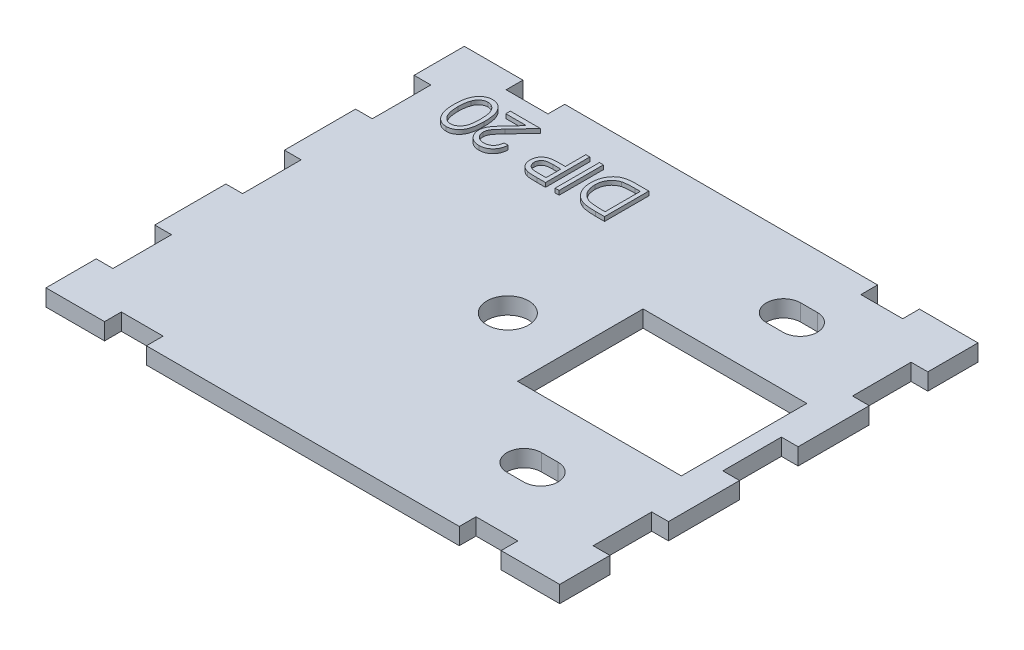
SolidWorks part; units mm, degrees
ref_plane "Front Plane" through (0, 0, 0) normal (0, 0, 1) x (1, 0, 0)
ref_plane "Top Plane" through (0, 0, 0) normal (0, 1, 0) x (1, 0, 0)
ref_plane "Right Plane" through (0, 0, 0) normal (1, 0, 0) x (0, 0, -1)
sketch "Sketch2" plane through (0, 0, 0) normal (0, 1, 0) x (1, 0, 0)
  line L1 (-50, 25) -> (50, 25)
  line L2 (-50, 25) -> (-50, -25)
  line L3 (-50, -25) -> (50, -25)
  line L4 (50, 25) -> (50, -25)
  line L5 (-50, 25) -> (50, -25) construction
  line L6 (-50, -25) -> (50, 25) construction
  point P0 (0, 0)
  dimension "D1" = 100
  dimension "D2" = 50
extrude "Boss-Extrude1" add sketch "Sketch2" along normal blind 2
sketch "Sketch12" plane through (0, 2, 0) normal (0, 1, 0) x (1, 0, 0)
  line L0 (-50, -25) -> (50, -25) construction
  line L1 (-40.2, -25) -> (-50, -25)
  line L2 (-40.2, -25) -> (-40.2, 25)
  line L3 (-40.2, 25) -> (-50, 25)
  line L4 (-50, -25) -> (-50, 25)
  line L5 (-50, -25) -> (50, -25) construction
  line L6 (41.2, -25) -> (50, -25)
  line L7 (41.2, -25) -> (41.2, 25)
  line L8 (41.2, 25) -> (50, 25)
  line L9 (50, -25) -> (50, 25)
extrude "Cut-Extrude8" cut sketch "Sketch12" against normal blind 6
sketch "Sketch13" plane through (0, 2, 0) normal (0, 1, 0) x (1, 0, 0)
  line L1 (-28.2, 19) -> (-30.2, 19)
  line L2 (-28.2, 19) -> (-28.2, 12)
  line L3 (-28.2, 12) -> (-30.2, 12)
  line L4 (-30.2, 19) -> (-30.2, 12)
  line L5 (-28.2, 3.5) -> (-30.2, 3.5)
  line L6 (-28.2, 3.5) -> (-28.2, -3.5)
  line L7 (-28.2, -3.5) -> (-30.2, -3.5)
  line L8 (-30.2, 3.5) -> (-30.2, -3.5)
  line L9 (-28.2, -12) -> (-30.2, -12)
  line L10 (-28.2, -12) -> (-28.2, -19)
  line L11 (-28.2, -19) -> (-30.2, -19)
  line L12 (-30.2, -12) -> (-30.2, -19)
  line L13 (29.2, 19) -> (31.2, 19)
  line L14 (29.2, 19) -> (29.2, 12)
  line L15 (29.2, 12) -> (31.2, 12)
  line L16 (31.2, 19) -> (31.2, 12)
  line L17 (29.2, 3.5) -> (31.2, 3.5)
  line L18 (29.2, 3.5) -> (29.2, -3.5)
  line L19 (29.2, -3.5) -> (31.2, -3.5)
  line L20 (31.2, 3.5) -> (31.2, -3.5)
  line L21 (29.2, -12) -> (31.2, -12)
  line L22 (29.2, -12) -> (29.2, -19)
  line L23 (29.2, -19) -> (31.2, -19)
  line L24 (31.2, -12) -> (31.2, -19)
  line L25 (-40.2, -25) -> (41.2, -25) construction
  line L26 (-23.2, 25) -> (-18.2, 25)
  line L27 (41.2, 25) -> (-40.2, 25) construction
  line L28 (-40.2, -25) -> (41.2, -25) construction
  line L29 (41.2, 25) -> (-40.2, 25) construction
  line L30 (-40.2, -25) -> (41.2, -25) construction
  line L31 (41.2, 25) -> (31.2, 25)
  line L32 (41.2, 25) -> (41.2, -25)
  line L33 (41.2, -25) -> (31.2, -25)
  line L34 (31.2, 25) -> (31.2, -25)
  line L35 (41.2, 25) -> (-40.2, 25) construction
  line L36 (-40.2, -25) -> (-30.2, -25)
  line L37 (-40.2, -25) -> (-40.2, 25)
  line L38 (-40.2, 25) -> (-30.2, 25)
  line L39 (-30.2, -25) -> (-30.2, 25)
  line L40 (-23.2, 25) -> (-23.2, 23)
  line L41 (-23.2, 23) -> (-18.2, 23)
  line L42 (-18.2, 25) -> (-18.2, 23)
  line L43 (-23.2, -25) -> (-18.2, -25)
  line L44 (-23.2, -25) -> (-23.2, -23)
  line L45 (-23.2, -23) -> (-18.2, -23)
  line L46 (-18.2, -25) -> (-18.2, -23)
  line L47 (24.2, -25) -> (19.2, -25)
  line L48 (24.2, -25) -> (24.2, -23)
  line L49 (24.2, -23) -> (19.2, -23)
  line L50 (19.2, -25) -> (19.2, -23)
  line L51 (24.2, 25) -> (19.2, 25)
  line L52 (24.2, 25) -> (24.2, 23)
  line L53 (24.2, 23) -> (19.2, 23)
  line L54 (19.2, 25) -> (19.2, 23)
  point P24 (29.2, 0)
  point P30 (30.2, 3.5)
  line M32 (41.2, -25) -> (41.2, 25)
  line M41 (41.2, 25) -> (-40.2, 25)
  line M42 (-40.2, 25) -> (-40.2, -25)
  line M47 (-40.2, -25) -> (41.2, -25)
  dimension "D1" = 2
  dimension "D2" = 2
  dimension "D3" = 2
  dimension "D4" = 2
  dimension "D5" = 2
  dimension "D6" = 2
  dimension "D7" = 57.4
  dimension "D8" = 57.4
  dimension "D9" = 57.4
  dimension "D10" = 7
  dimension "D11" = 7
  dimension "D12" = 7
  dimension "D13" = 7
  dimension "D14" = 7
  dimension "D15" = 7
  dimension "D16" = 5
  dimension "D17" = 2
  dimension "D18" = 5
  dimension "D19" = 6
  dimension "D20" = 8.5
  dimension "D21" = 8.5
  dimension "D22" = 6
  dimension "D23" = 6
  dimension "D24" = 8.5
  dimension "D25" = 8.5
  dimension "D26" = 6
  dimension "D27" = 5
  dimension "D28" = 5
  dimension "D29" = 2
  dimension "D30" = 2
  dimension "D31" = 5
  dimension "D32" = 5
  dimension "D33" = 5
  dimension "D34" = 5
  dimension "D35" = 2
extrude "Cut-Extrude10" cut sketch "Sketch13" against normal blind 6 contours L5 L8 L7 L6 | L39 L12 L8 L4 M47 M41 M42 | L1 L4 L3 L2 | L50 L48 L49 M47 | L24 L21 L22 L23 | L20 L17 L18 L19 | L16 L13 L14 L15 | L54 L53 L52 M41 | L9 L12 L11 L10 | L34 L16 L20 L24 M41 M47 M32 | L26 L42 L41 L40 | L45 L46 L43 L44
sketch "Sketch15" plane through (0, 0, 0) normal (0, -1, 0) x (1, 0, 0)
  line L0 (24.2, 23) -> (19.2, 23) construction
  line L1 (31.2, -12) -> (31.2, -3.5) construction
  line L16 (20.7242, -7.5) -> (20.7242, -8.5)
  line L17 (20.7242, -7.5) -> (25.936, -7.5)
  line L18 (25.936, -7.5) -> (25.936, 5.5)
  line L19 (25.936, 5.5) -> (8.9693, 5.5)
  line L20 (8.9693, 5.5) -> (8.9693, -7.5)
  line L21 (8.9693, -7.5) -> (14.1811, -7.5)
  line L22 (14.1811, -7.5) -> (14.1811, -8.5)
  line L23 (14.1811, -8.5) -> (7.6661, -8.5)
  line L24 (7.6661, -8.5) -> (7.6661, 6.5)
  line L25 (7.6661, 6.5) -> (27.2392, 6.5)
  line L26 (27.2392, 6.5) -> (27.2392, -8.5)
  line L27 (27.2392, -8.5) -> (20.7242, -8.5)
  line L28 (20.7242, -8.5) -> (14.1811, -8.5)
  line L29 (14.1811, -7.5) -> (20.7242, -7.5)
  dimension "D1" = 13
  dimension "D4" = 16.5
  dimension "D5" = 6.5431
  dimension "D6" = 90
  dimension "D7" = 3.9608
  dimension "D8" = 90
  dimension "D9" = 1.3032
  dimension "D24" = 5.2118
  dimension "D25" = 5.2118
  dimension "D26" = 6.515
  dimension "D27" = 6.515
  dimension "D28" = 1
  dimension "D31" = 90
  dimension "D32" = 90
  dimension "D34" = 1
extrude "Cut-Extrude13" cut sketch "Sketch15" against normal blind 10 contours L21 L29 L17 L18 L19 L20 | L27 L26 L25 L24 L23 L22 L21 L20 L19 L18 L17 L16 | L29 L22 L28 L16
sketch "Sketch16" plane through (0, 0, 0) normal (0, -1, 0) x (-1, 0, 0)
  circle A0 centre (0, 0) radius 2.5
  dimension "D1" = 5
extrude "Cut-Extrude14" cut sketch "Sketch16" against normal blind 10 contours A0
sketch "Sketch17" plane through (0, 0, 0) normal (0, -1, 0) x (-1, 0, 0)
  line L0 (-16.4527, 18.55) -> (-18.4527, 18.55)
  line L1 (-16.4527, 14.45) -> (-18.4527, 14.45)
  line L2 (-27.2392, 8.5) -> (-7.6661, 8.5) construction
  line L3 (-16.4527, -12.45) -> (-18.4527, -12.45)
  line L4 (-7.6661, -6.5) -> (-27.2392, -6.5) construction
  line L5 (-18.4527, -16.55) -> (-16.4527, -16.55)
  circle A0 centre (-17.4527, -14.5) radius 2.05
  circle A1 centre (-17.4527, 16.5) radius 2.05
  circle A2 centre (-16.4527, 16.5) radius 2.05
  circle A3 centre (-18.4527, 16.5) radius 2.05
  circle A4 centre (-18.4527, -14.5) radius 2.05
  circle A5 centre (-16.4527, -14.5) radius 2.05
  dimension "D1" = 4.1
  dimension "D2" = 4.1
  dimension "D9" = 1
  dimension "D10" = 0
  dimension "D12" = 0
  dimension "D15" = 0
  dimension "D16" = 0
  dimension "D3" = 8
  dimension "D4" = 9.7866
  dimension "D5" = 9.7866
  dimension "D6" = 9.7866
  dimension "D7" = 9.7866
  dimension "D8" = 8
  dimension "D11" = 1
  dimension "D13" = 1
  dimension "D14" = 1
extrude "Cut-Extrude15" cut sketch "Sketch17" against normal blind 3.5 contours A4 A0 | A5 A4 A0 | A4 A5 | A0 A5 A4 | A5 A0 | A5 L3 A0 | A5 A0 A4 | A4 A0 L3 | A5 A0 L5 | A5 A4 A0 | A4 L5 A0 | A2 A3 | A1 A3 A2 | A3 A1 | A3 A2 A1 | A3 A1 A2 | A3 A2 A1 | A2 A1 | A2 A1 L1 | A3 L1 A1 | A3 A1 L0 | A2 L0 A1
sketch "Sketch22" plane through (0, 2, 0) normal (0, 1, 0) x (1, 0, 0)
  line L0 (-24.5837, 20.5398) -> (4.8961, 20.5398) construction
  text T0 "DIP 20" font "Century Gothic" height in points 20
extrude "Boss-Extrude4" add sketch "Sketch22" along normal blind 0.5
